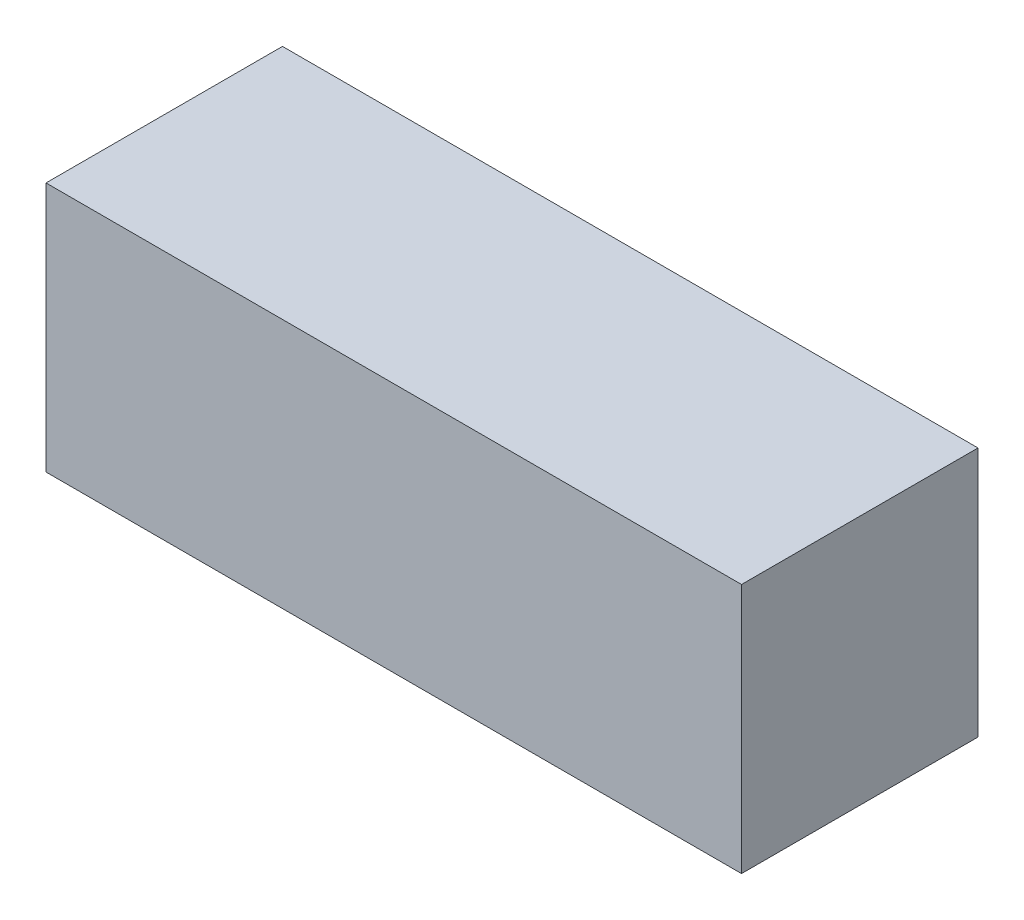
SolidWorks part; units mm, degrees
ref_plane "Front Plane" through (0, 0, 0) normal (0, 0, 1) x (1, 0, 0)
ref_plane "Top Plane" through (0, 0, 0) normal (0, 1, 0) x (1, 0, 0)
ref_plane "Right Plane" through (0, 0, 0) normal (1, 0, 0) x (0, 0, -1)
sketch "Sketch1" plane through (0, 0, 0) normal (0, 1, 0) x (1, 0, 0)
  line L1 (-635, -215.9) -> (635, -215.9)
  line L2 (-635, -215.9) -> (-635, 215.9)
  line L3 (-635, 215.9) -> (635, 215.9)
  line L4 (635, -215.9) -> (635, 215.9)
  line L5 (-635, -215.9) -> (635, 215.9) construction
  line L6 (-635, 215.9) -> (635, -215.9) construction
  point P0 (0, 0)
  dimension "D1" = 431.8
  dimension "D2" = 1270
extrude "Boss-Extrude1" add sketch "Sketch1" along normal blind 457.2
